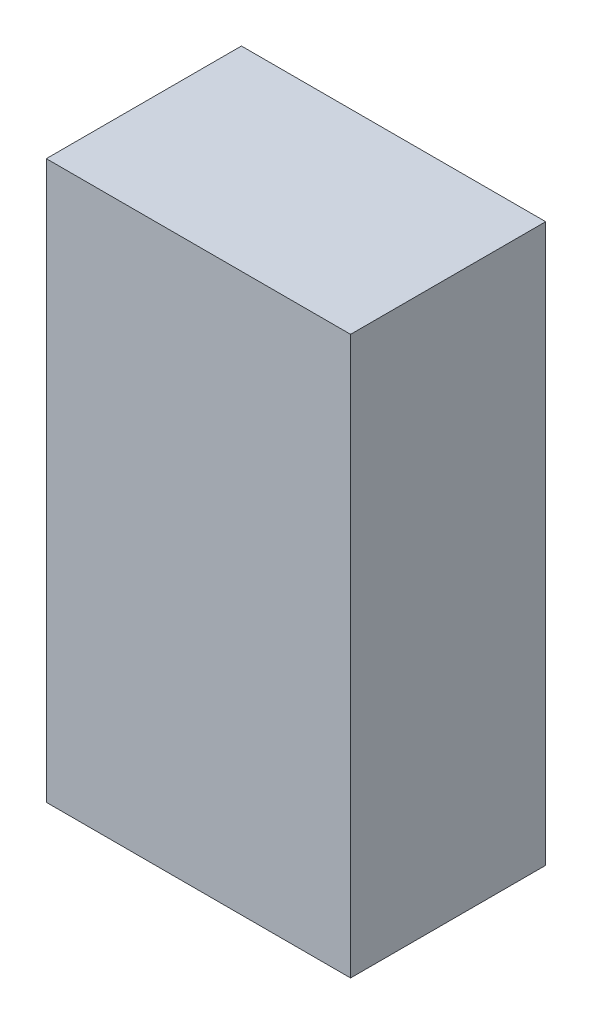
SolidWorks part; units mm, degrees
ref_plane "Front Plane" through (0, 0, 0) normal (0, 0, 1) x (1, 0, 0)
ref_plane "Top Plane" through (0, 0, 0) normal (0, 1, 0) x (1, 0, 0)
ref_plane "Right Plane" through (0, 0, 0) normal (1, 0, 0) x (0, 0, -1)
sketch "Sketch1" plane through (0, 0, 0) normal (0, 1, 0) x (1, 0, 0)
  line L1 (-13.1, -8.4) -> (13.1, -8.4)
  line L2 (-13.1, -8.4) -> (-13.1, 8.4)
  line L3 (-13.1, 8.4) -> (13.1, 8.4)
  line L4 (13.1, -8.4) -> (13.1, 8.4)
  line L5 (-13.1, -8.4) -> (13.1, 8.4) construction
  line L6 (-13.1, 8.4) -> (13.1, -8.4) construction
  point P0 (0, 0)
  dimension "D1" = 16.8
  dimension "D2" = 26.2
extrude "Boss-Extrude1" add sketch "Sketch1" along normal blind 48
